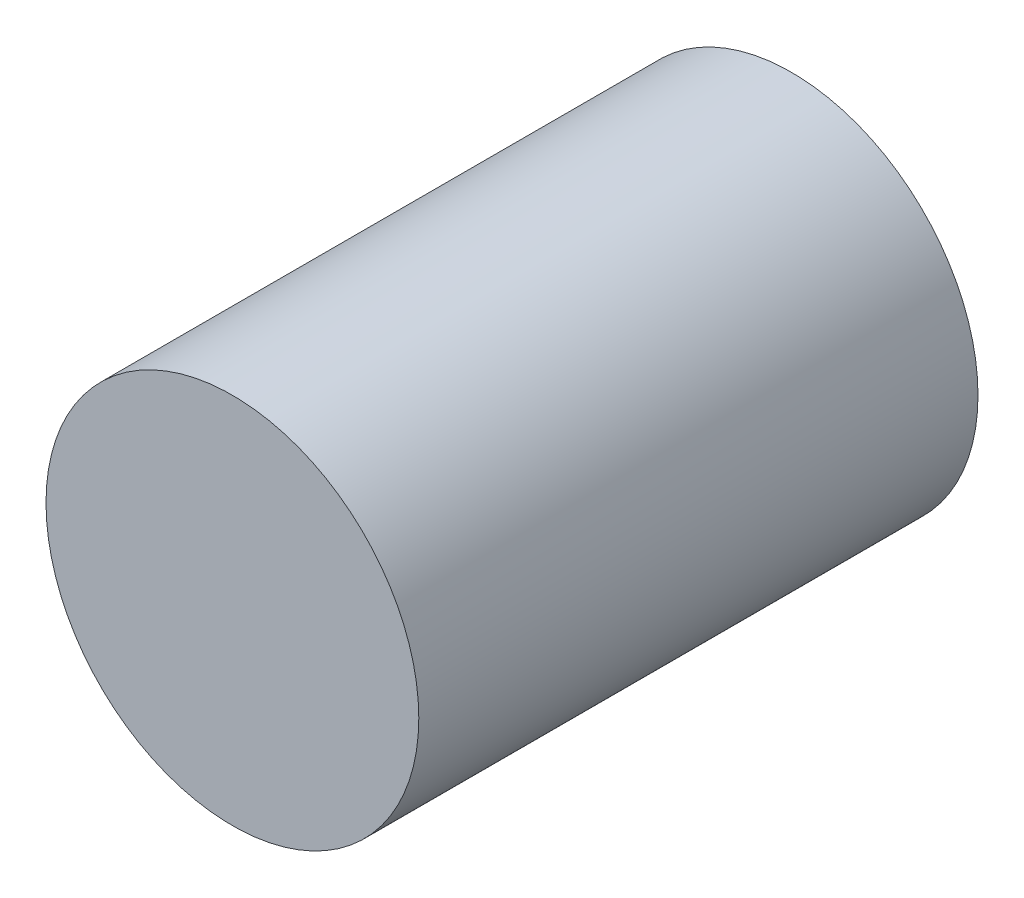
SolidWorks part; units mm, degrees
material "Alloy Steel"
ref_plane "Front Plane" through (0, 0, 0) normal (0, 0, 1) x (1, 0, 0)
ref_plane "Top Plane" through (0, 0, 0) normal (0, 1, 0) x (1, 0, 0)
ref_plane "Right Plane" through (0, 0, 0) normal (1, 0, 0) x (0, 0, -1)
sketch "Sketch2" plane through (0, 0, 0) normal (0, 0, 1) x (1, 0, 0)
  circle A0 centre (0, 0) radius 1
  dimension "D1" = 2
extrude "Boss-Extrude1" add sketch "Sketch2" along normal blind 3
